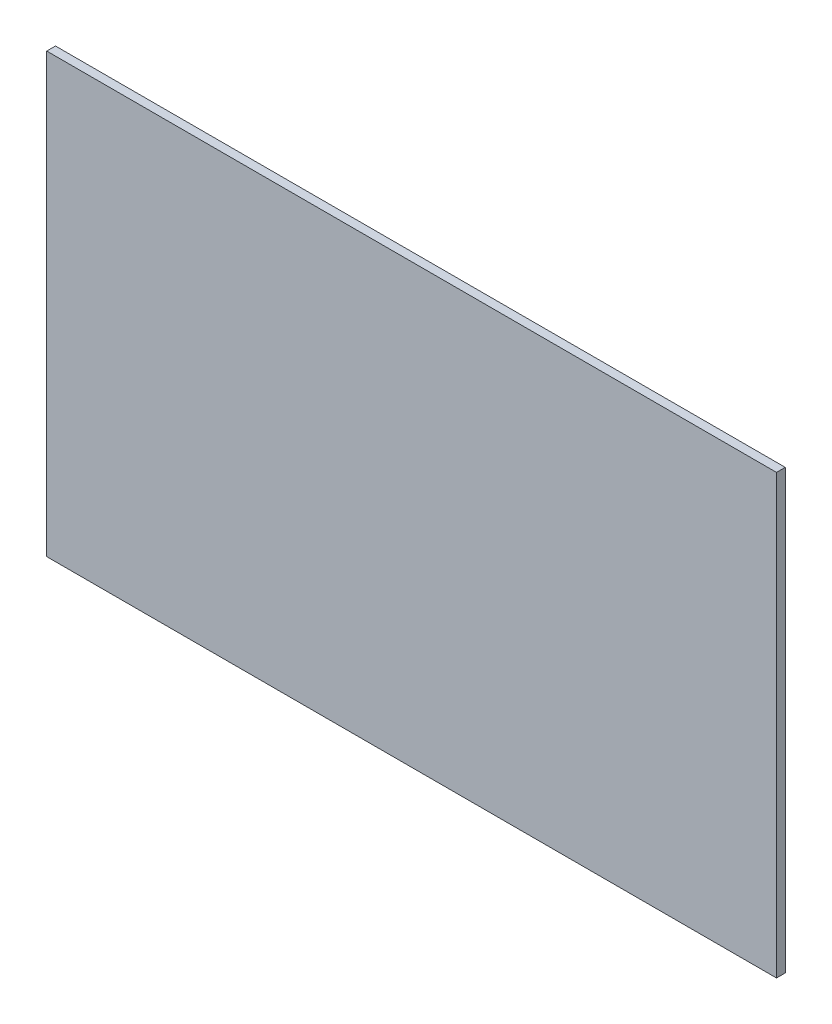
SolidWorks part; units mm, degrees
ref_plane "Спереди" through (0, 0, 0) normal (0, 0, 1) x (1, 0, 0)
ref_plane "Сверху" through (0, 0, 0) normal (0, 1, 0) x (1, 0, 0)
ref_plane "Справа" through (0, 0, 0) normal (1, 0, 0) x (0, 0, -1)
sketch "Эскиз1" plane through (0, 0, 0) normal (0, 0, 1) x (1, 0, 0)
  line L1 (-105.5759, 55.3016) -> (144.4241, 55.3016)
  line L2 (-105.5759, 55.3016) -> (-105.5759, -94.6984)
  line L3 (-105.5759, -94.6984) -> (144.4241, -94.6984)
  line L4 (144.4241, 55.3016) -> (144.4241, -94.6984)
  dimension "D1" = 250
  dimension "D2" = 150
extrude "Бобышка-Вытянуть1" add sketch "Эскиз1" along normal blind 3
sketch "Эскиз2" plane through (0, 0, 3) normal (0, 0, 1) x (1, 0, 0)
  line L0 (144.4241, 55.3016) -> (-105.5759, 55.3016) construction
  line L1 (-105.5759, -94.6984) -> (144.4241, -94.6984)
  line L2 (-105.5759, -94.6984) -> (-105.5759, -91.6984)
  line L3 (-105.5759, -91.6984) -> (144.4241, -91.6984)
  line L4 (144.4241, -94.6984) -> (144.4241, -91.6984)
  line L5 (144.4241, -94.6984) -> (139.4221, -94.6984)
  line L6 (144.4241, -94.6984) -> (144.4241, 55.3016)
  line L7 (144.4241, 55.3016) -> (139.4221, 55.3016)
  line L8 (139.4221, -94.6984) -> (139.4221, 55.3016)
  dimension "D1" = 250
  dimension "D2" = 3
